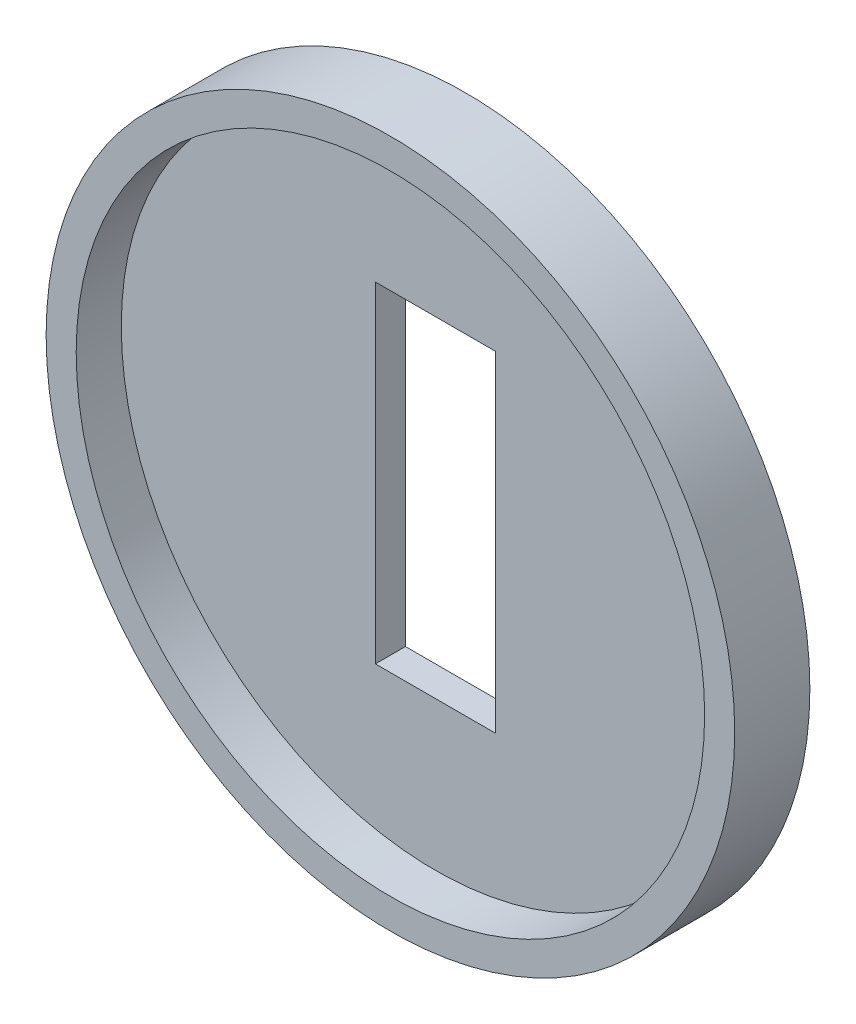
SolidWorks part; units mm, degrees
ref_plane "Ebene vorne" through (0, 0, 0) normal (0, 0, 1) x (1, 0, 0)
ref_plane "Ebene oben" through (0, 0, 0) normal (0, 1, 0) x (1, 0, 0)
ref_plane "Ebene rechts" through (0, 0, 0) normal (1, 0, 0) x (0, 0, -1)
sketch "Skizze1" plane through (0, 0, 0) normal (0, 1, 0) x (1, 0, 0)
  line L0 (0, 0) -> (22.902, 0)
  line L1 (22.902, 0) -> (22.902, -5)
  line L2 (22.902, -5) -> (20.902, -5)
  line L3 (20.902, -5) -> (20.902, -2)
  line L4 (20.902, -2) -> (0, -2)
  line L5 (0, -2) -> (0, 0)
revolve "Rotation2" add sketch "Skizze1" angle 360 about L5
sketch "Skizze2" plane through (0, 0, 0) normal (0, 0, -1) x (-1, 0, 0)
  line L0 (0, 0) -> (4, 0)
  line L4 (4, 11) -> (-4, 11)
  line L5 (-4, 11) -> (-4, -11)
  line L6 (4, 11) -> (4, -11)
  line L7 (4, -11) -> (-4, -11)
extrude "Schnitt-Linear austragen1" cut sketch "Skizze2" against normal blind 10
